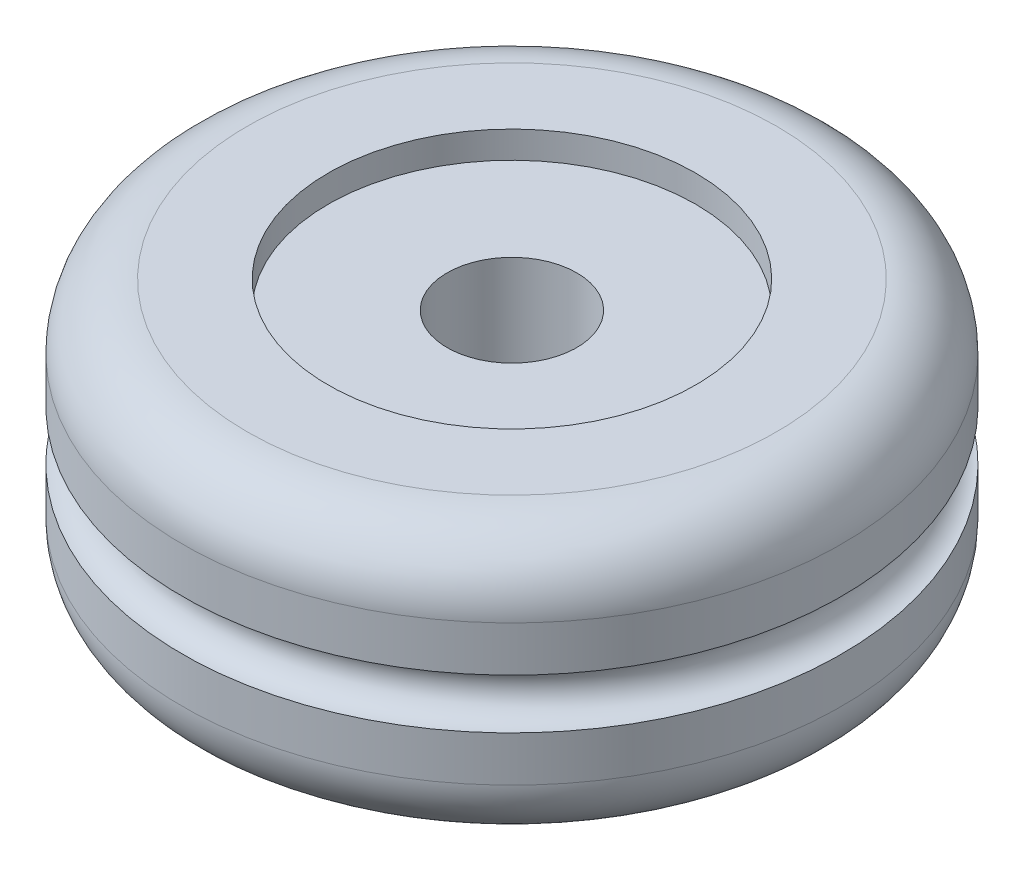
SolidWorks part; units mm, degrees
ref_plane "Спереди" through (0, 0, 0) normal (0, 0, 1) x (1, 0, 0)
ref_plane "Сверху" through (0, 0, 0) normal (0, 1, 0) x (1, 0, 0)
ref_plane "Справа" through (0, 0, 0) normal (1, 0, 0) x (0, 0, -1)
sketch "Эскиз1" plane through (0, 0, 0) normal (0, 0, 1) x (1, 0, 0)
  line L0 (0, 26.126) -> (0, 70.2062) construction
  line L1 (17, 0) -> (24.5, 0)
  line L2 (6, 2.5) -> (6, 22.5)
  line L3 (17, 25) -> (24.5, 25)
  line L4 (30.5, 19) -> (30.5, 14.8132)
  line L5 (30.5, 10.1868) -> (30.5, 6)
  line L6 (6, 22.5) -> (17, 22.5)
  line L7 (30.5, 12.5) -> (6, 12.5) construction
  line L8 (17, 22.5) -> (17, 25)
  line L9 (6, 2.5) -> (17, 2.5)
  line L10 (17, 2.5) -> (17, 0)
  arc A1 (24.5, 25) -> (30.5, 19) centre (24.5, 19) cw
  arc A2 (24.5, 0) -> (30.5, 6) centre (24.5, 6) ccw
  arc A3 (30.5, 14.8132) -> (30.5, 10.1868) centre (30.5, 12.5) ccw
  point P9 (30.5, 25)
  point P12 (30.5, 0)
  dimension "D3" = 6
  dimension "D8" = 2.3132
  dimension "D1" = 7.5
  dimension "D2" = 7.5
  dimension "D4" = 4.1868
  dimension "D5" = 2.5
  dimension "D6" = 11
  dimension "D7" = 4.1868
  dimension "D9" = 20
  dimension "D10" = 6
revolve "Повернуть1" add sketch "Эскиз1" angle 360 about L0
